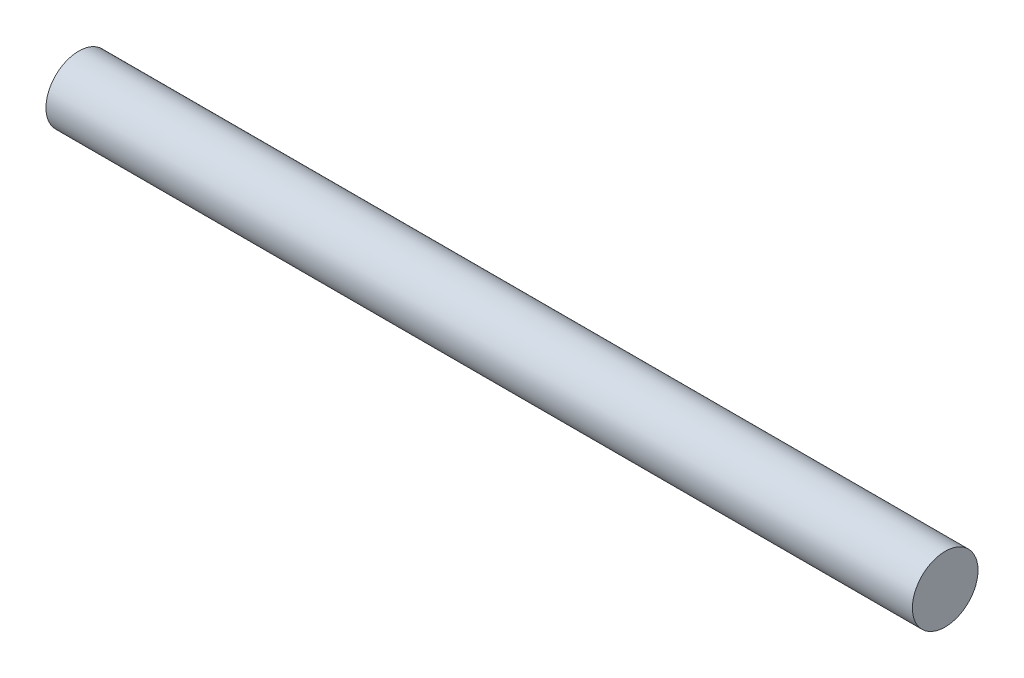
SolidWorks part; units mm, degrees
ref_plane "Спереди" through (0, 0, 0) normal (0, 0, 1) x (1, 0, 0)
ref_plane "Сверху" through (0, 0, 0) normal (0, 1, 0) x (1, 0, 0)
ref_plane "Справа" through (0, 0, 0) normal (1, 0, 0) x (0, 0, -1)
sketch "Профіль вала" plane through (0, 0, 0) normal (1, 0, 0) x (0, 0, -1)
  circle A0 centre (0, 0) radius 75
  dimension "Діаметр" = 150
extrude "Вал" add sketch "Профіль вала" along normal blind 1980
equation "\"Довжина@Вал\" = 1980.0"
